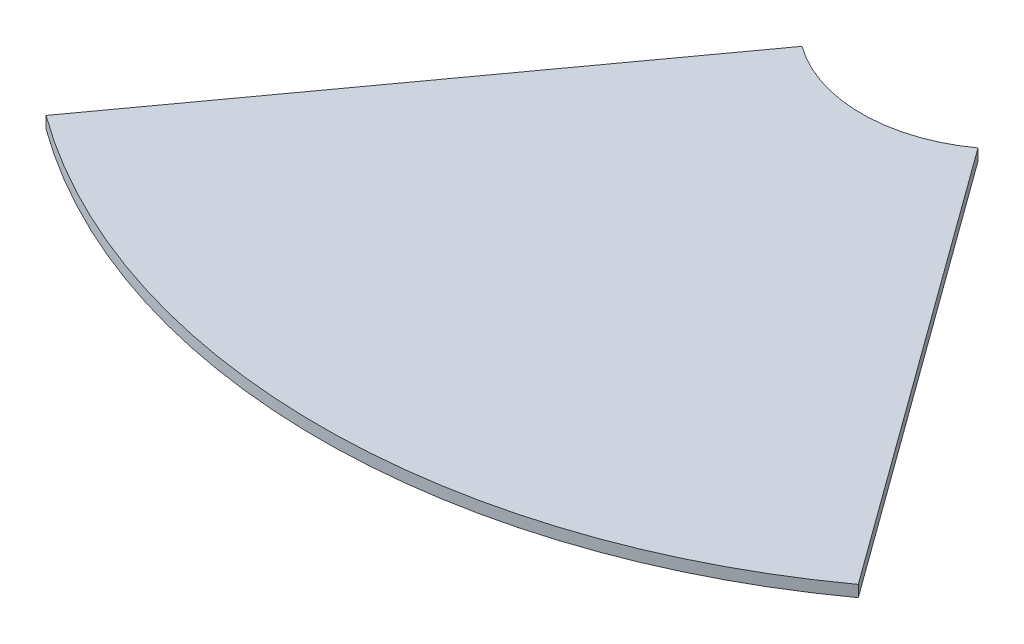
SolidWorks part; units mm, degrees
ref_plane "Front Plane" through (0, 0, 0) normal (0, 0, 1) x (1, 0, 0)
ref_plane "Top Plane" through (0, 0, 0) normal (0, 1, 0) x (1, 0, 0)
ref_plane "Right Plane" through (0, 0, 0) normal (1, 0, 0) x (0, 0, -1)
sketch "Sketch1" plane through (0, 0, 0) normal (0, 1, 0) x (1, 0, 0)
  line L2 (38.206, -52.5861) -> (176.3356, -242.7051)
  line L3 (-38.206, -52.5861) -> (-176.3356, -242.7051)
  arc A0 (-176.3356, -242.7051) -> (176.3356, -242.7051) centre (0, 0) ccw
  arc A2 (-38.206, -52.5861) -> (38.206, -52.5861) centre (0, 0) ccw
  point P6 (-37.929, -52.2048)
  point P11 (38.206, -52.5861)
  dimension "D1" = 600
  dimension "D4" = 130
extrude "Boss-Extrude1" add sketch "Sketch1" along normal blind 5
